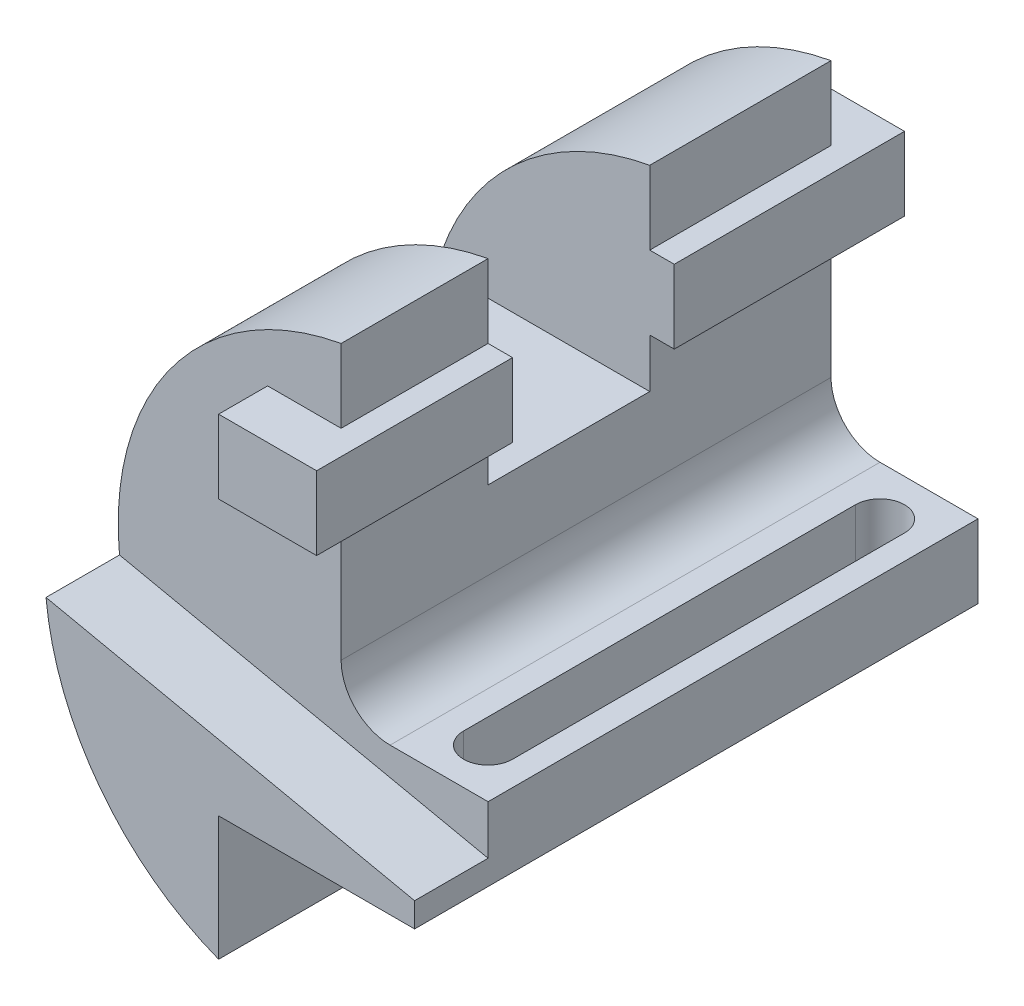
SolidWorks part; units mm, degrees
material "1060 Alloy"
ref_plane "Front Plane" through (0, 0, 0) normal (0, 0, 1) x (1, 0, 0)
ref_plane "Top Plane" through (0, 0, 0) normal (0, 1, 0) x (1, 0, 0)
ref_plane "Right Plane" through (0, 0, 0) normal (1, 0, 0) x (0, 0, -1)
sketch "Sketch1" plane through (0, 0, 0) normal (0, 0, 1) x (1, 0, 0)
  line L0 (0, 0) -> (-40, 0)
  line L1 (-40, 0) -> (-40, -25.3628)
  line L2 (0, 0) -> (0, 15)
  line L3 (0, 15) -> (-30, 15)
  line L4 (-30, 15) -> (-30, 81)
  arc A0 (-30, 81) -> (-40, -25.3628) centre (-20, 26.4083) ccw
  dimension "D4" = 55.5
  dimension "D1" = 40
  dimension "D2" = 15
  dimension "D3" = 30
  dimension "D5" = 10
  dimension "D6" = 66
extrude "Boss-Extrude1" add sketch "Sketch1" along normal blind 115
sketch "Sketch2" plane through (0, 0, 115) normal (0, 0, 1) x (1, 0, 0)
  line L0 (0, 5) -> (-75.235, 20.9917)
  line L1 (0, 0) -> (0, 15) construction
  line L2 (-40, 0) -> (0, 0) construction
  line L8 (0, 0) -> (0, 15)
  line L9 (0, 15) -> (-30, 15)
  line L10 (-30, 15) -> (-30, 81)
  line L11 (-40, -25.3628) -> (-40, 0)
  line L12 (-40, 0) -> (0, 0)
  line L13 (0, 5) -> (0, 15)
  line L14 (0, 15) -> (-30, 15)
  line L15 (-30, 15) -> (-30, 81)
  arc A1 (-30, 81) -> (-40, -25.3628) centre (-20, 26.4083) ccw
  arc A2 (-30, 81) -> (-75.235, 20.9917) centre (-20, 26.4083) ccw
  dimension "D1" = 78
  dimension "D2" = 5
  dimension "D3" = 0
extrude "Cut-Extrude1" cut sketch "Sketch2" against normal blind 15
sketch "Sketch3" plane through (0, 0, 0) normal (0, 0, -1) x (-1, 0, 0)
  line L0 (30, 15) -> (30, 81) construction
  line L1 (25, 66) -> (45, 66)
  line L2 (25, 66) -> (25, 51)
  line L3 (25, 51) -> (45, 51)
  line L4 (45, 66) -> (45, 51)
  dimension "D1" = 15
  dimension "D2" = 15
  dimension "D3" = 20
  dimension "D4" = 5
extrude "Boss-Extrude2" add sketch "Sketch3" against normal offset from surface 5 and the other way blind 10 up to face at (-32.3604, -0.8725, 115)
sketch "Sketch4" plane through (-30, 0, 0) normal (1, 0, 0) x (0, 0, -1)
  line L0 (-100, 81) -> (0, 81) construction
  line L1 (-70, 81) -> (-37, 81)
  line L2 (-70, 81) -> (-70, 41)
  line L3 (-70, 41) -> (-37, 41)
  line L4 (-37, 81) -> (-37, 41)
  line L5 (-100, 66) -> (-100, 81) construction
  line L6 (-100, 51) -> (0, 51) construction
  dimension "D1" = 30
  dimension "D2" = 33
  dimension "D3" = 10
extrude "Cut-Extrude2" cut sketch "Sketch4" against normal through all both and the other way through all
sketch "Sketch5" plane through (0, 15, 0) normal (0, 1, 0) x (1, 0, 0)
  line L0 (-10, -10) -> (-10, -90) construction
  line L1 (-5, -10) -> (-5, -90)
  line L2 (-15, -10) -> (-15, -90)
  line L3 (0, 0) -> (-30, 0) construction
  line L6 (0, -100) -> (0, 0) construction
  arc A0 (-5, -10) -> (-15, -10) centre (-10, -10) ccw
  arc A1 (-15, -90) -> (-5, -90) centre (-10, -90) ccw
  point P2 (-10, -50)
  dimension "D1" = 80
  dimension "D2" = 10
  dimension "D3" = 10
  dimension "D4" = 10
extrude "Cut-Extrude3" cut sketch "Sketch5" against normal through all
fillet "Fillet1" radius 10 1 edges at (-30, 15, 50)
equation "\"a\"= 55.5"
equation "\"b\"= 66"
equation "\"c\"= 33"
